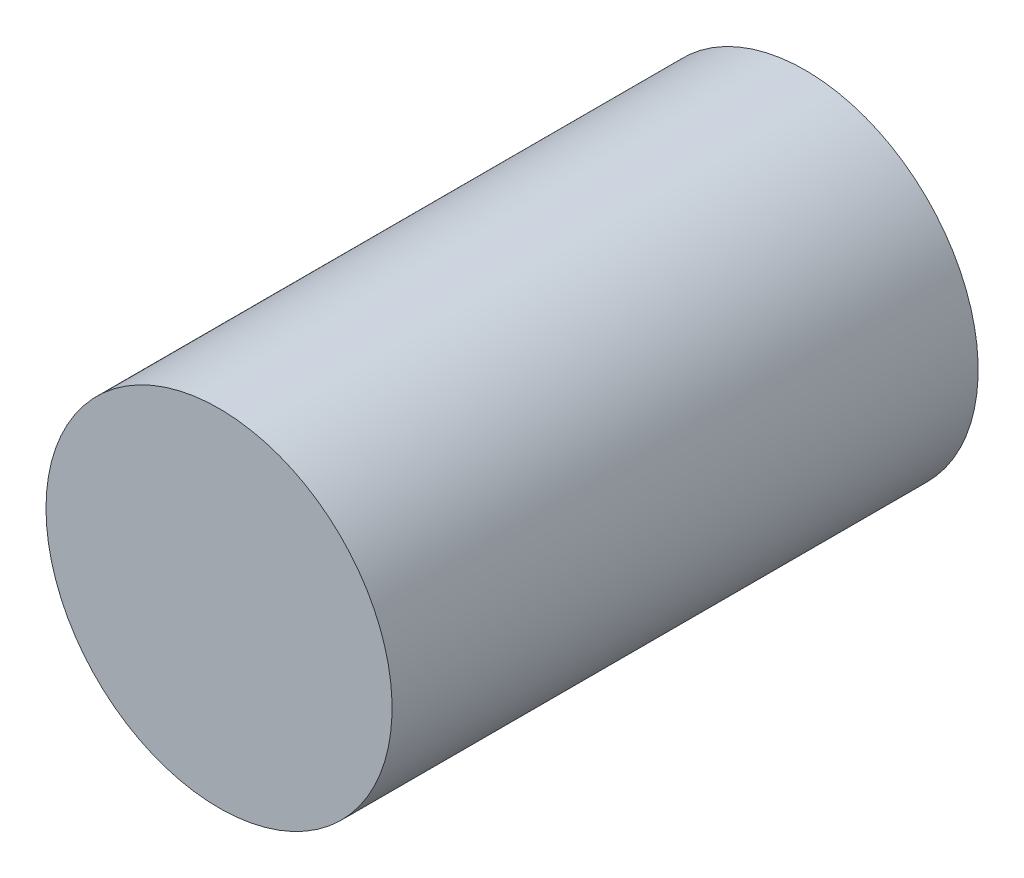
SolidWorks part; units mm, degrees
ref_plane "Front Plane" through (0, 0, 0) normal (0, 0, 1) x (1, 0, 0)
ref_plane "Top Plane" through (0, 0, 0) normal (0, 1, 0) x (1, 0, 0)
ref_plane "Right Plane" through (0, 0, 0) normal (1, 0, 0) x (0, 0, -1)
sketch "Sketch1" plane through (0, 0, 0) normal (0, 0, 1) x (1, 0, 0)
  circle A0 centre (0, 0) radius 6.2
extrude "Envelope" add sketch "Sketch1" along normal blind 21
